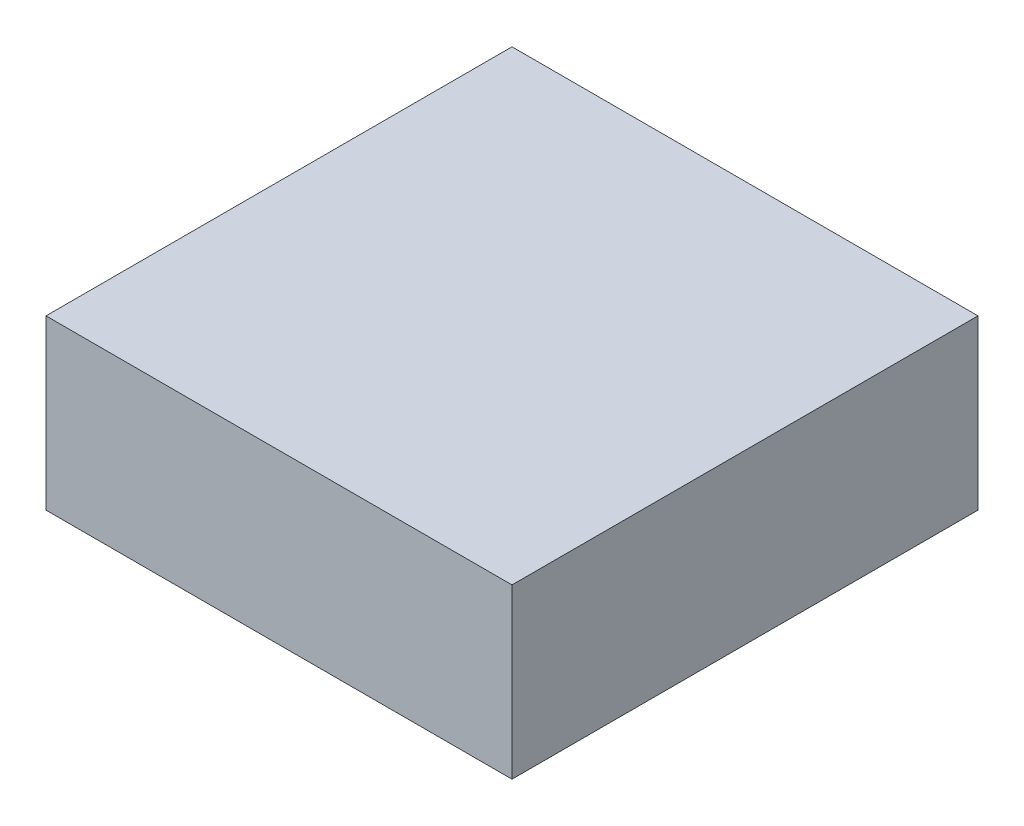
SolidWorks part; units mm, degrees
ref_plane "Alzado" through (0, 0, 0) normal (0, 0, 1) x (1, 0, 0)
ref_plane "Planta" through (0, 0, 0) normal (0, 1, 0) x (1, 0, 0)
ref_plane "Vista lateral" through (0, 0, 0) normal (1, 0, 0) x (0, 0, -1)
sketch "Croquis2" plane through (0, 0, 0) normal (0, 1, 0) x (1, 0, 0)
  line L1 (-6.75, 6.75) -> (6.75, 6.75)
  line L2 (-6.75, 6.75) -> (-6.75, -6.75)
  line L3 (-6.75, -6.75) -> (6.75, -6.75)
  line L4 (6.75, 6.75) -> (6.75, -6.75)
  line L5 (-6.75, 6.75) -> (6.75, -6.75) construction
  line L6 (-6.75, -6.75) -> (6.75, 6.75) construction
  line L7 (-9, 9) -> (9, 9)
  line L8 (-9, 9) -> (-9, -9)
  line L9 (-9, -9) -> (9, -9)
  line L10 (9, 9) -> (9, -9)
  line L11 (-9, 9) -> (9, -9) construction
  line L12 (-9, -9) -> (9, 9) construction
  point P0 (0, 0)
  point P6 (0, 0)
  dimension "D1" = 13.5
  dimension "D2" = 13.5
  dimension "D3" = 18
  dimension "D4" = 18
extrude "Saliente-Extruir1" add sketch "Croquis2" along normal blind 5
sketch "Croquis3" plane through (0, 5, 0) normal (0, 1, 0) x (1, 0, 0)
  line L1 (-9, 9) -> (9, 9)
  line L2 (-9, 9) -> (-9, -9)
  line L3 (-9, -9) -> (9, -9)
  line L4 (9, 9) -> (9, -9)
  line L5 (-9, 9) -> (9, -9) construction
  line L6 (-9, -9) -> (9, 9) construction
  point P0 (0, 0)
extrude "Saliente-Extruir2" add sketch "Croquis3" along normal blind 1.5
